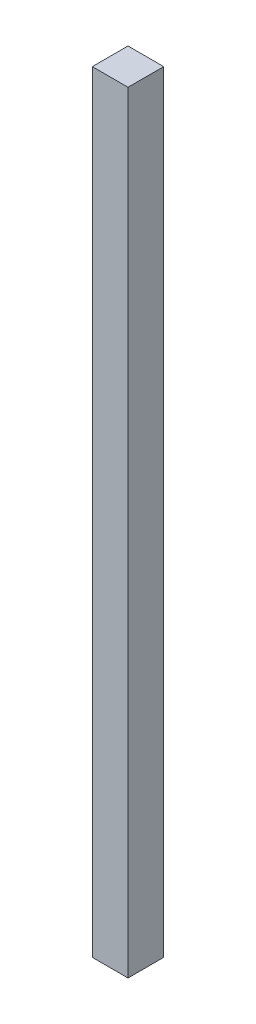
SolidWorks part; units mm, degrees
ref_plane "Front Plane" through (0, 0, 0) normal (0, 0, 1) x (1, 0, 0)
ref_plane "Top Plane" through (0, 0, 0) normal (0, 1, 0) x (1, 0, 0)
ref_plane "Right Plane" through (0, 0, 0) normal (1, 0, 0) x (0, 0, -1)
sketch "Sketch1" plane through (0, 0, 0) normal (0, 1, 0) x (1, 0, 0)
  line L1 (0, 0) -> (-25, 0)
  line L2 (0, 0) -> (0, -25)
  line L3 (0, -25) -> (-25, -25)
  line L4 (-25, 0) -> (-25, -25)
  dimension "D1" = 25
  dimension "D2" = 25
extrude "Boss-Extrude1" add sketch "Sketch1" along normal blind 540
